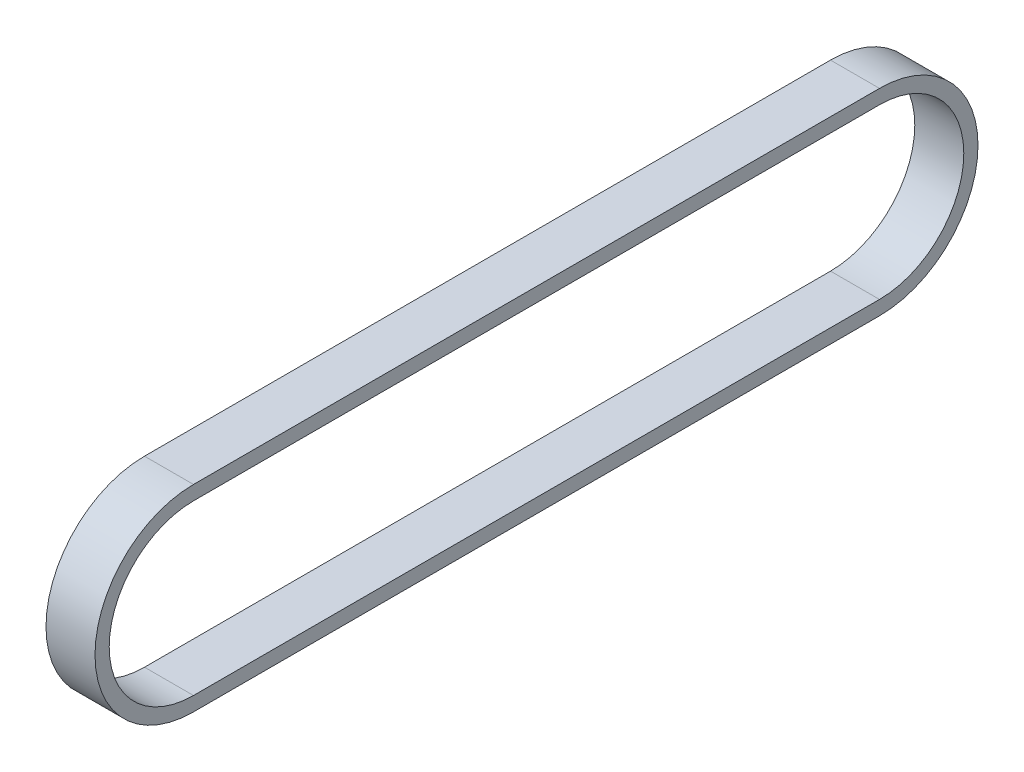
SolidWorks part; units mm, degrees
material "Rubber"
ref_plane "Front Plane" through (0, 0, 0) normal (0, 0, 1) x (1, 0, 0)
ref_plane "Top Plane" through (0, 0, 0) normal (0, 1, 0) x (1, 0, 0)
ref_plane "Right Plane" through (0, 0, 0) normal (1, 0, 0) x (0, 0, -1)
sketch "Sketch1" plane through (0, 0, 0) normal (1, 0, 0) x (0, 0, -1)
  line L0 (0, 25.527) -> (177.8, 25.527)
  line L1 (0, 21.844) -> (177.8, 21.844)
  line L2 (0, -21.844) -> (177.8, -21.844)
  line L3 (0, -25.527) -> (177.8, -25.527)
  arc A0 (0, 21.844) -> (0, -21.844) centre (0, 0) ccw
  arc A1 (0, 25.527) -> (0, -25.527) centre (0, 0) ccw
  arc A2 (177.8, -25.527) -> (177.8, 25.527) centre (177.8, 0) ccw
  arc A3 (177.8, -21.844) -> (177.8, 21.844) centre (177.8, 0) ccw
  dimension "D1" = 21.844
  dimension "D2" = 3.683
  dimension "D3" = 177.8
extrude "Boss-Extrude1" add sketch "Sketch1" along normal blind 12.7
